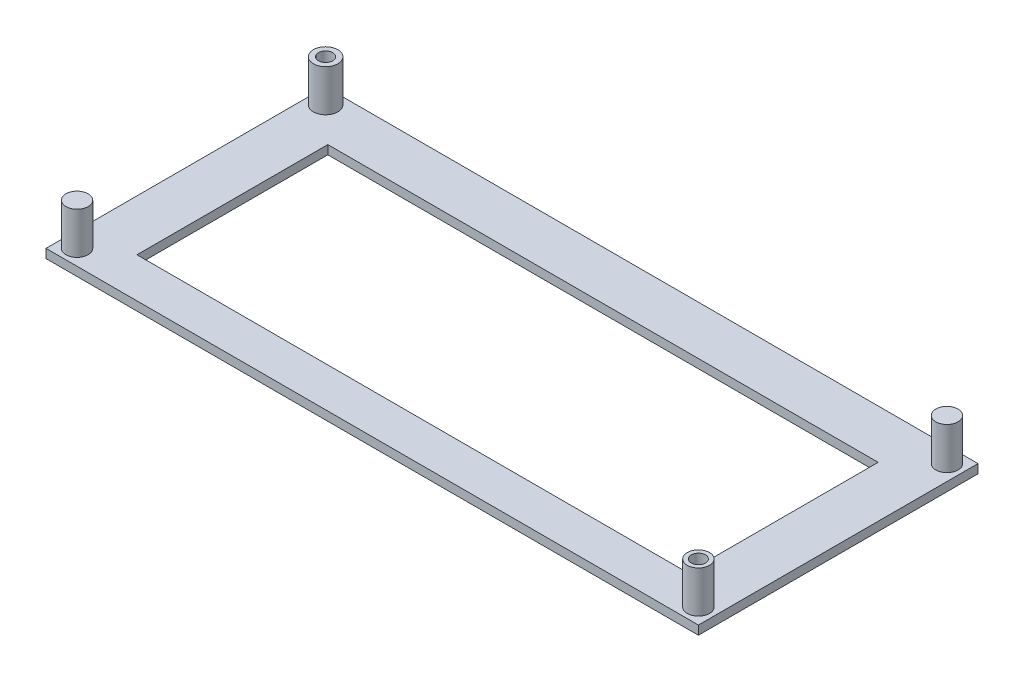
SolidWorks part; units mm, degrees
ref_plane "Ebene vorne" through (0, 0, 0) normal (0, 0, 1) x (1, 0, 0)
ref_plane "Ebene oben" through (0, 0, 0) normal (0, 1, 0) x (1, 0, 0)
ref_plane "Ebene rechts" through (0, 0, 0) normal (1, 0, 0) x (0, 0, -1)
sketch "Skizze3" plane through (0, 0, 0) normal (0, 1, 0) x (1, 0, 0)
  line L0 (0, 0) -> (147, 0)
  line L1 (147, 0) -> (147, 63)
  line L2 (147, 63) -> (0, 63)
  line L3 (0, 63) -> (0, 0)
  dimension "D1" = 63
  dimension "D2" = 147
extrude "Aufsatz-Linear austragen2" add sketch "Skizze3" along normal blind 2
sketch "Skizze4" plane through (0, 2, 0) normal (0, 1, 0) x (1, 0, 0)
  line L0 (11.5, 52) -> (11.5, 9)
  line L1 (11.5, 9) -> (135.5, 9)
  line L2 (135.5, 9) -> (135.5, 52)
  line L3 (135.5, 52) -> (11.5, 52)
  line L4 (147, 63) -> (0, 63) construction
  line L5 (0, 0) -> (147, 0) construction
  line L6 (0, 63) -> (0, 0) construction
  line L7 (147, 0) -> (147, 63) construction
  dimension "D1" = 11
  dimension "D2" = 9
  dimension "D3" = 11.5
  dimension "D4" = 11.5
extrude "Schnitt-Linear austragen1" cut sketch "Skizze4" against normal blind 2
sketch "Skizze5" plane through (0, 2, 0) normal (0, 1, 0) x (1, 0, 0)
  line L0 (147, 63) -> (0, 63) construction
  line L1 (0, 63) -> (0, 0) construction
  circle A0 centre (3.5, 59.5) radius 2.7524
  dimension "D1" = 3.5
  dimension "D2" = 3.5
extrude "Aufsatz-Linear austragen3" add sketch "Skizze5" along normal blind 9.4
sketch "Skizze6" plane through (0, 11.4, 0) normal (0, 1, 0) x (1, 0, 0)
  circle A0 centre (3.5, 59.5) radius 1.6
extrude "Schnitt-Linear austragen2" cut sketch "Skizze6" against normal blind 11.4
sketch "Skizze7" plane through (0, 2, 0) normal (0, 1, 0) x (1, 0, 0)
  line L0 (147, 0) -> (147, 63) construction
  line L1 (0, 0) -> (147, 0) construction
  circle A0 centre (143.5, 3.5) radius 2.5
  dimension "D1" = 3.5
  dimension "D2" = 3.5
extrude "Aufsatz-Linear austragen4" add sketch "Skizze7" along normal blind 9.4
sketch "Skizze8" plane through (0, 11.4, 0) normal (0, 1, 0) x (1, 0, 0)
  circle A0 centre (143.5, 3.5) radius 1.6
extrude "Schnitt-Linear austragen3" cut sketch "Skizze8" against normal blind 11.4
sketch "Skizze9" plane through (0, 2, 0) normal (0, 1, 0) x (1, 0, 0)
  line L0 (0, 63) -> (0, 0) construction
  line L1 (0, 0) -> (147, 0) construction
  line L2 (147, 0) -> (147, 63) construction
  line L3 (147, 63) -> (0, 63) construction
  circle A0 centre (143.5, 59.5) radius 2.5
  circle A1 centre (3.5, 3.5) radius 2.5
  dimension "D1" = 5
  dimension "D2" = 5
  dimension "D3" = 3.5
  dimension "D4" = 3.5
  dimension "D5" = 3.5
  dimension "D6" = 3.5
extrude "Aufsatz-Linear austragen5" add sketch "Skizze9" along normal blind 9.4
